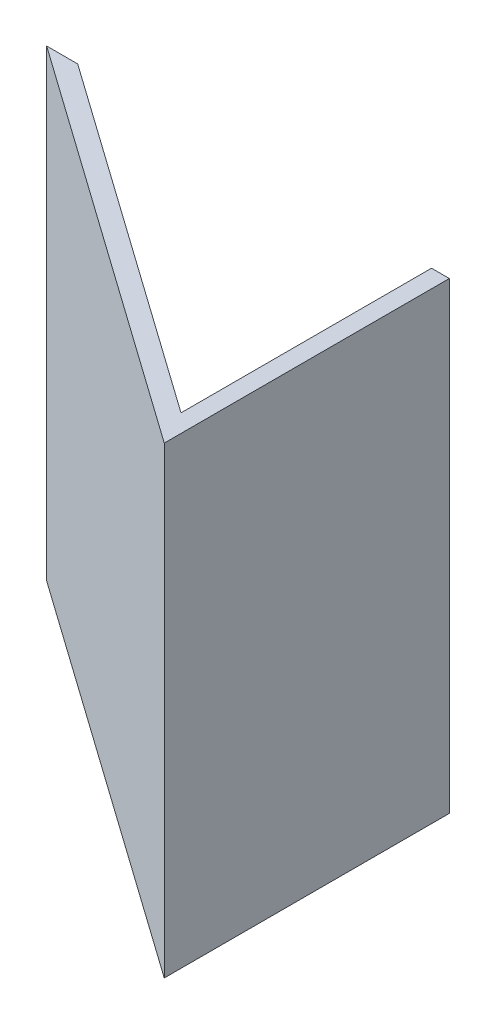
SolidWorks part; units mm, degrees
ref_plane "Front Plane" through (0, 0, 0) normal (0, 0, 1) x (1, 0, 0)
ref_plane "Top Plane" through (0, 0, 0) normal (0, 1, 0) x (1, 0, 0)
ref_plane "Right Plane" through (0, 0, 0) normal (1, 0, 0) x (0, 0, -1)
sketch "Sketch1" plane through (0, 0, 0) normal (0, 1, 0) x (1, 0, 0)
  line L1 (65.0271, 34.1908) -> (65.0271, -16.6092)
  line L2 (-6.7279, 34.1908) -> (65.0271, -16.6092)
  line L3 (-6.7279, 34.1908) -> (-1.2008, 34.1908)
  line L4 (65.0271, 34.1908) -> (61.8521, 34.1908)
  line L5 (61.8521, 34.1908) -> (61.8521, -10.4497)
  line L15 (-1.2008, 34.1908) -> (61.8521, -10.4497)
extrude "Boss-Extrude1" add sketch "Sketch1" along normal blind 82.55
